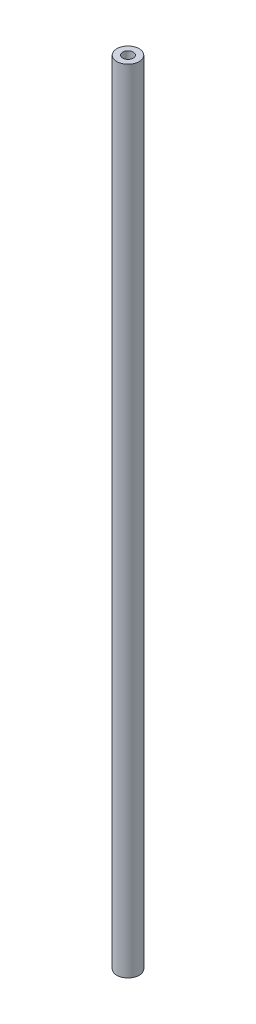
SolidWorks part; units mm, degrees
ref_plane "Front Plane" through (0, 0, 0) normal (0, 0, 1) x (1, 0, 0)
ref_plane "Top Plane" through (0, 0, 0) normal (0, 1, 0) x (1, 0, 0)
ref_plane "Right Plane" through (0, 0, 0) normal (1, 0, 0) x (0, 0, -1)
sketch "Croquis2" plane through (0, 0, 0) normal (0, 1, 0) x (1, 0, 0)
  circle A0 centre (0, 0) radius 6.35
extrude "Saliente-Extruir1" add sketch "Croquis2" along normal blind 450
sketch "Croquis3" plane through (0, 450, 0) normal (0, 1, 0) x (1, 0, 0)
  circle A0 centre (0, 0) radius 3
extrude "Cortar-Extruir1" cut sketch "Croquis3" against normal blind 24
sketch "Croquis4" plane through (0, 0, 0) normal (0, -1, 0) x (-1, 0, 0)
  circle A0 centre (0, 0) radius 3
extrude "Cortar-Extruir2" cut sketch "Croquis4" against normal blind 24
